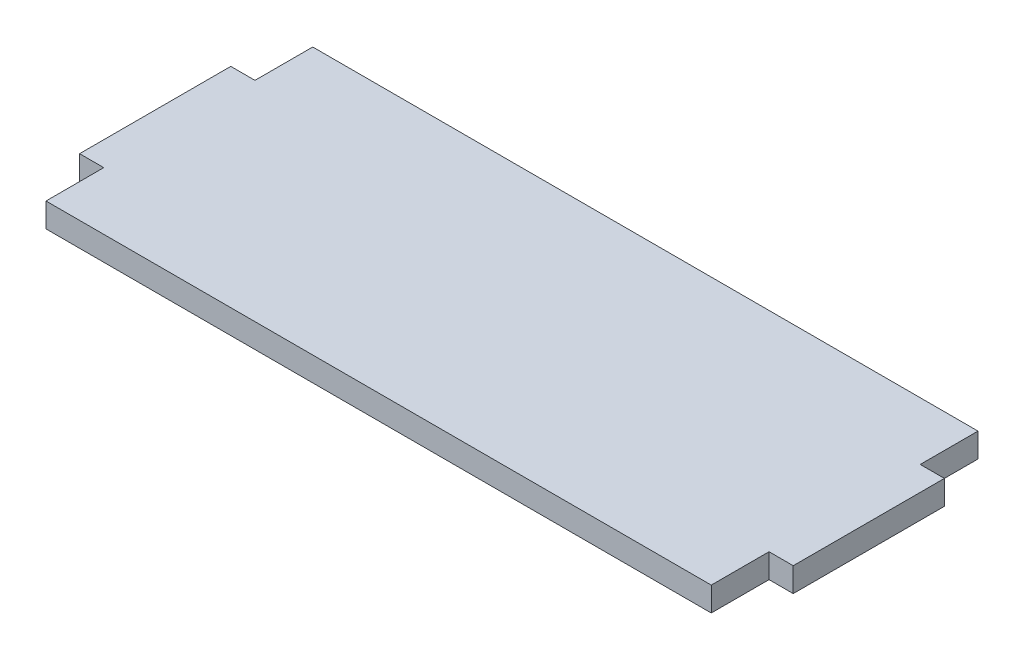
SolidWorks part; units mm, degrees
ref_plane "Front Plane" through (0, 0, 0) normal (0, 0, 1) x (1, 0, 0)
ref_plane "Top Plane" through (0, 0, 0) normal (0, 1, 0) x (1, 0, 0)
ref_plane "Right Plane" through (0, 0, 0) normal (1, 0, 0) x (0, 0, -1)
sketch "Sketch1" plane through (0, 0, 0) normal (0, 1, 0) x (1, 0, 0)
  line L0 (110, 88.21) -> (110, 0) construction
  line L1 (0, 0) -> (220, 0)
  line L2 (0, 0) -> (0, 88.21)
  line L3 (0, 88.21) -> (220, 88.21)
  line L4 (220, 0) -> (220, 88.21)
  line L5 (-8, 69.105) -> (0, 69.105)
  line L6 (-8, 69.105) -> (-8, 19.105)
  line L7 (-8, 19.105) -> (0, 19.105)
  line L8 (0, 69.105) -> (0, 19.105)
  line L9 (228, 19.105) -> (220, 19.105)
  line L10 (220, 69.105) -> (220, 19.105)
  line L11 (228, 69.105) -> (220, 69.105)
  line L12 (228, 69.105) -> (228, 19.105)
  point P9 (0, 44.105)
  point P10 (0, 44.105)
  dimension "D1" = 88.21
  dimension "D2" = 220
  dimension "D3" = 8
  dimension "D4" = 50
extrude "Boss-Extrude1" add sketch "Sketch1" along normal blind 8 contours L6 L7 L2 L5 | L0 L3 L2 L1 | L3 L0 L1 L4 | L12 L11 L4 L9
